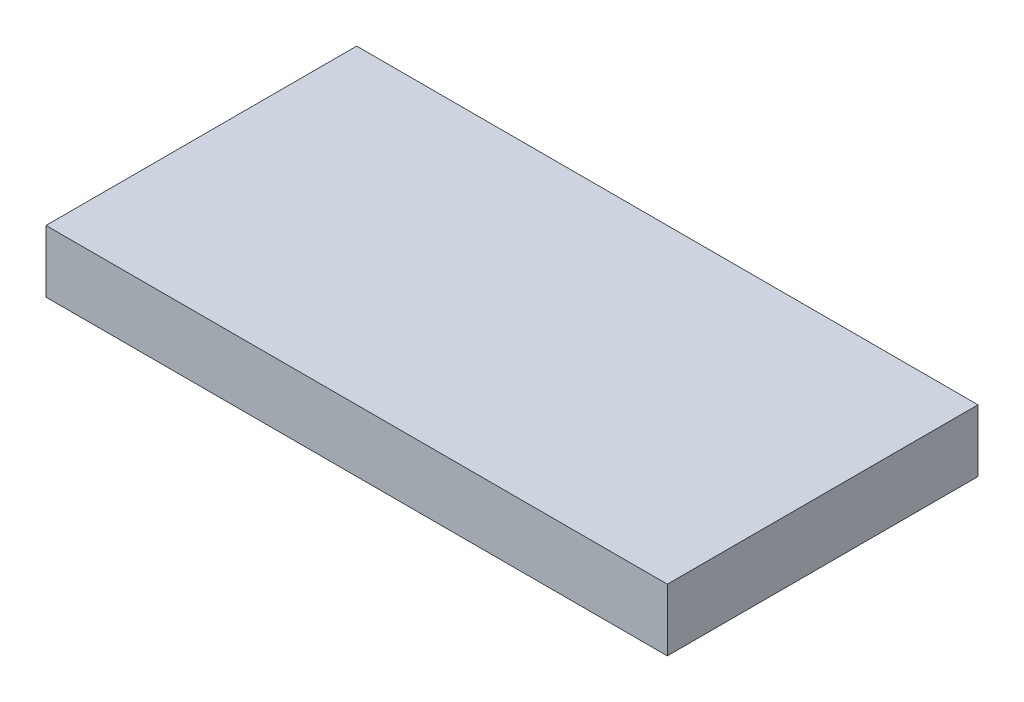
SolidWorks part; units mm, degrees
ref_plane "Front Plane" through (0, 0, 0) normal (0, 0, 1) x (1, 0, 0)
ref_plane "Top Plane" through (0, 0, 0) normal (0, 1, 0) x (1, 0, 0)
ref_plane "Right Plane" through (0, 0, 0) normal (1, 0, 0) x (0, 0, -1)
sketch "Sketch1" plane through (0, 0, 0) normal (0, 1, 0) x (1, 0, 0)
  line L1 (0, 0) -> (40, 0)
  line L2 (0, 0) -> (0, 20)
  line L3 (0, 20) -> (40, 20)
  line L4 (40, 0) -> (40, 20)
extrude "Boss-Extrude1" add sketch "Sketch1" along normal blind 4
